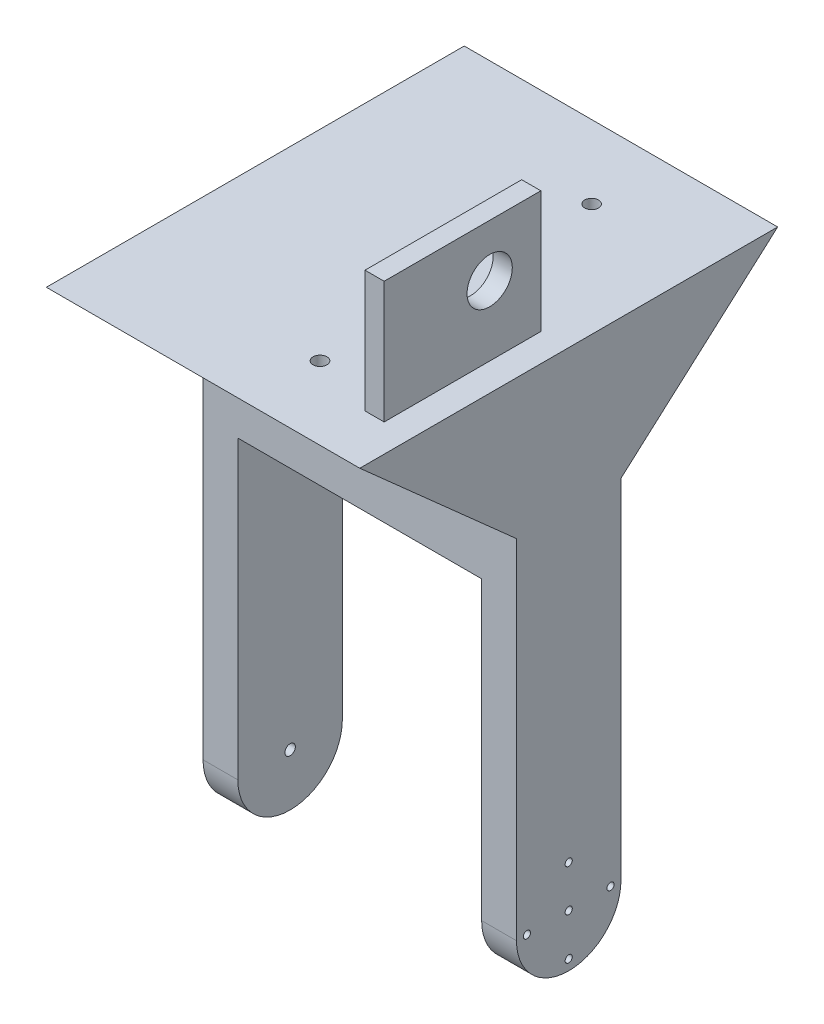
SolidWorks part; units mm, degrees
material "Nylon 101"
ref_plane "Front Plane" through (0, 0, 0) normal (0, 0, 1) x (1, 0, 0)
ref_plane "Top Plane" through (0, 0, 0) normal (0, 1, 0) x (1, 0, 0)
ref_plane "Right Plane" through (0, 0, 0) normal (1, 0, 0) x (0, 0, -1)
sketch "Sketch1" plane through (0, 0, 0) normal (1, 0, 0) x (0, 0, -1)
  line L0 (0, 0) -> (0, 63.602) construction
  line L1 (15, 11.5967) -> (15, 111.5967)
  line L2 (-15, 11.5967) -> (-15, 111.5967)
  line L3 (-15, 111.5967) -> (15, 111.5967)
  arc A0 (-15, 11.5967) -> (15, 11.5967) centre (0, 11.5967) ccw
  dimension "D3" = 100
  dimension "D1" = 15
  dimension "D2" = 15
extrude "Boss-Extrude1" add sketch "Sketch1" against normal blind 10
sketch "Sketch4" plane through (-10, 0, 0) normal (-1, 0, 0) x (0, 0, 1)
  line L0 (15, 111.5967) -> (15, 11.5967) construction
  line L1 (-15, 111.5967) -> (15, 111.5967)
  line L2 (-15, 111.5967) -> (-15, 96.5967)
  line L3 (-15, 96.5967) -> (15, 96.5967)
  line L4 (15, 111.5967) -> (15, 96.5967)
  dimension "D1" = 15
extrude "Boss-Extrude2" add sketch "Sketch4" along normal blind 70
sketch "Sketch5" plane through (-80, 0, 0) normal (-1, 0, 0) x (0, 0, 1)
  line L0 (-15, 111.5967) -> (15, 111.5967)
  line L1 (15, 96.5967) -> (15, 111.5967) construction
  line L2 (15, 111.5967) -> (-15, 111.5967) construction
  line L3 (15, 111.5967) -> (15, 11.5967)
  line L4 (-15, 111.5967) -> (-15, 11.5967)
  line L5 (-15, 11.5967) -> (-15, 96.5967) construction
  arc A0 (-15, 11.5967) -> (15, 11.5967) centre (0, 11.5967) ccw construction
  arc A1 (-15, 11.5967) -> (15, 11.5967) centre (0, 11.5967) ccw
extrude "Boss-Extrude3" add sketch "Sketch5" along normal blind 10
sketch "Sketch6" plane through (-10, 0, 0) normal (-1, 0, 0) x (0, 0, 1)
  line L0 (-15, 11.5967) -> (-15, 96.5967) construction
  circle A0 centre (0, 11.5967) radius 6.05
  circle A1 centre (0, 23.5967) radius 1
  arc A3 (-15, 11.5967) -> (15, 11.5967) centre (0, 11.5967) ccw construction
  dimension "D1" = 12.1
  dimension "D2" = 2
  dimension "D3" = 12
  dimension "D4" = 15
  dimension "D5" = 0
sketch "Sketch10" plane through (-90, 0, 0) normal (-1, 0, 0) x (0, 0, 1)
  circle A0 centre (0, 11.5967) radius 1.5
extrude "Cut-Extrude3" cut sketch "Sketch6" against normal blind 3 contours A0
sketch "Sketch7" plane through (-10, 0, 0) normal (-1, 0, 0) x (0, 0, 1)
  circle A0 centre (0, 23.5967) radius 1.025
  circle A1 centre (0, 11.5967) radius 6.05 construction
  circle A2 centre (12, 11.5967) radius 1.025
  circle A3 centre (0, -0.4033) radius 1.025
  circle A4 centre (-12, 11.5967) radius 1.025
  circle A5 centre (0, 11.5967) radius 1.025
  point P14 (0, 11.5967)
  dimension "D1" = 2.05
  dimension "D2" = 12
  dimension "D4" = 2.05
  dimension "D3" = 4
extrude "Cut-Extrude4" cut sketch "Sketch7" against normal through all
sketch "Sketch9" plane through (-90, 0, 0) normal (-1, 0, 0) x (0, 0, 1)
  line L0 (15, 11.5967) -> (15, 111.5967) construction
  line L1 (34.4904, -55.0681) -> (-47.0569, 32.9661) construction
  circle A0 centre (0, 11.5967) radius 1.5
  dimension "D1" = 3
  dimension "D3" = 20
  dimension "D2" = 15
extrude "Cut-Extrude9" cut sketch "Sketch10" against normal up to surface (10 mm away) up to face at (-80, 50.3467, 0)
sketch "Sketch14" plane through (-90, 0, 0) normal (-1, 0, 0) x (0, 0, 1)
  line L0 (-15, 111.5967) -> (-60, 151.5967)
  line L1 (-60, 151.5967) -> (60, 151.5967)
  line L2 (60, 151.5967) -> (15, 111.5967)
  line L3 (15, 111.5967) -> (-15, 111.5967)
  dimension "D1" = 120
  dimension "D2" = 40
extrude "Boss-Extrude4" add sketch "Sketch14" against normal blind 90
sketch "Sketch15" plane through (0, 151.5967, 0) normal (0, 1, 0) x (1, 0, 0)
  line L1 (-8, -45) -> (-13.5, -45)
  line L2 (-8, -45) -> (-8, 0)
  line L3 (-8, 0) -> (-13.5, 0)
  line L4 (-13.5, -45) -> (-13.5, 0)
  line L5 (0, -60) -> (-90, -60) construction
  line L7 (0, -60) -> (0, 60) construction
  dimension "D1" = 5.5
  dimension "D2" = 45
  dimension "D3" = 15
  dimension "D4" = 8
extrude "Boss-Extrude5" add sketch "Sketch15" along normal blind 35
sketch "Sketch16" plane through (-8, 0, 0) normal (1, 0, 0) x (0, 0, -1)
  line L2 (0, 186.5967) -> (0, 151.5967) construction
  line L3 (-60, 151.5967) -> (60, 151.5967) construction
  circle A2 centre (-14.7, 171.5967) radius 6.5
  dimension "D1" = 14.7
  dimension "D2" = 13
  dimension "D3" = 20
extrude "Cut-Extrude10" cut sketch "Sketch16" against normal up to surface (5.5 mm away) up to face at (-13.5, 169.0967, 22.5)
sketch "Sketch17" plane through (0, 151.5967, 0) normal (0, 1, 0) x (1, 0, 0)
  circle A0 centre (-32.4216, 39) radius 2
  circle A1 centre (-32.4216, -39) radius 2
extrude "Cut-Extrude11" cut sketch "Sketch17" against normal blind 34
